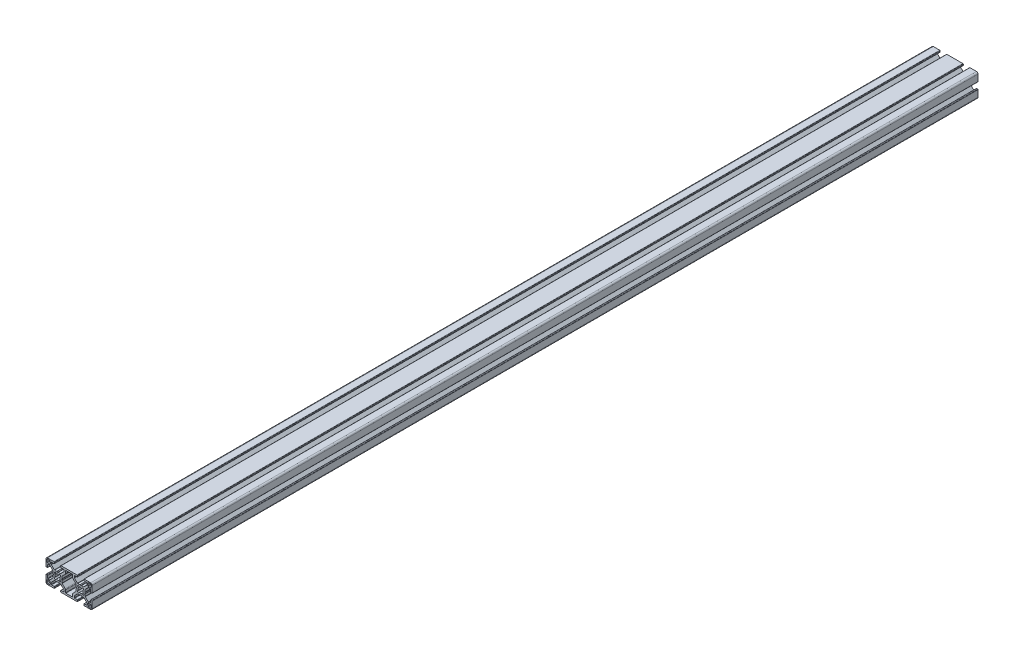
SolidWorks part; units mm, degrees
material "6105-T5 Aluminum"
ref_plane "Front Plane" through (0, 0, 0) normal (0, 0, 1) x (1, 0, 0)
ref_plane "Top Plane" through (0, 0, 0) normal (0, 1, 0) x (1, 0, 0)
ref_plane "Right Plane" through (0, 0, 0) normal (1, 0, 0) x (0, 0, -1)
sketch "Sketch1" plane through (0, 0, 0) normal (0, 0, 1) x (1, 0, 0)
  line L0 (12.7825, 3.7261) -> (13.5257, 2.983)
  line L1 (16.4743, 2.983) -> (17.2175, 3.7261)
  line L2 (18.7261, 2.2175) -> (17.983, 1.4743)
  line L3 (17.983, -1.4743) -> (18.7261, -2.2175)
  line L4 (17.2175, -3.7261) -> (16.4743, -2.983)
  line L5 (13.5257, -2.983) -> (12.7825, -3.7261)
  line L6 (11.2739, -2.2175) -> (12.017, -1.4743)
  line L7 (12.017, 1.4743) -> (11.2739, 2.2175)
  line L8 (-28.7046, 9.8946) -> (-28.7046, 12.6886)
  line L9 (-27.6886, 13.7046) -> (-24.8946, 13.7046)
  line L10 (-24.5136, 13.3236) -> (-24.5136, 9.8946)
  line L11 (-24.8946, 9.5136) -> (-28.3236, 9.5136)
  line L12 (-24.8946, -13.7046) -> (-27.6886, -13.7046)
  line L13 (-28.7046, -12.6886) -> (-28.7046, -9.8946)
  line L14 (-28.3236, -9.5136) -> (-24.8946, -9.5136)
  line L15 (-24.5136, -9.8946) -> (-24.5136, -13.3236)
  line L16 (4.9816, 8.2224) -> (9.0292, 4.1748)
  line L17 (9.178, 3.8155) -> (9.178, 0.9525)
  line L18 (9.178, 0.9525) -> (9.686, 0)
  line L19 (9.686, 0) -> (9.178, -0.9525)
  line L20 (9.178, -0.9525) -> (9.178, -3.8155)
  line L21 (9.0292, -4.1748) -> (4.9816, -8.2224)
  line L22 (4.5352, -9.3) -> (4.5352, -12.4092)
  line L23 (4.1542, -12.7902) -> (-4.1542, -12.7902)
  line L24 (-4.5352, -12.4092) -> (-4.5352, -9.3)
  line L25 (-4.9816, -8.2224) -> (-9.0292, -4.1748)
  line L26 (-9.178, -3.8155) -> (-9.178, -0.9525)
  line L27 (-9.178, -0.9525) -> (-9.686, 0)
  line L28 (-9.686, 0) -> (-9.178, 0.9525)
  line L29 (-9.178, 0.9525) -> (-9.178, 3.8155)
  line L30 (-9.0292, 4.1748) -> (-4.9816, 8.2224)
  line L31 (-4.5352, 9.3) -> (-4.5352, 12.4092)
  line L32 (-4.1542, 12.7902) -> (4.1542, 12.7902)
  line L33 (4.5352, 12.4092) -> (4.5352, 9.3)
  line L34 (-18.7261, -2.2175) -> (-17.983, -1.4743)
  line L35 (-17.983, 1.4743) -> (-18.7261, 2.2175)
  line L36 (-17.2175, 3.7261) -> (-16.4743, 2.983)
  line L37 (-13.5257, 2.983) -> (-12.7825, 3.7261)
  line L38 (-11.2739, 2.2175) -> (-12.017, 1.4743)
  line L39 (-12.017, -1.4743) -> (-11.2739, -2.2175)
  line L40 (-12.7825, -3.7261) -> (-13.5257, -2.983)
  line L41 (-16.4743, -2.983) -> (-17.2175, -3.7261)
  line L42 (24.8946, 13.7046) -> (27.6886, 13.7046)
  line L43 (28.7046, 12.6886) -> (28.7046, 9.8946)
  line L44 (28.3236, 9.5136) -> (24.8946, 9.5136)
  line L45 (24.5136, 9.8946) -> (24.5136, 13.3236)
  line L46 (24.5136, -13.3236) -> (24.5136, -9.8946)
  line L47 (24.8946, -9.5136) -> (28.3236, -9.5136)
  line L48 (28.7046, -9.8946) -> (28.7046, -12.6886)
  line L49 (27.6886, -13.7046) -> (24.8946, -13.7046)
  line L50 (-10.428, -15) -> (10.428, -15)
  line L51 (10.936, -14.492) -> (10.936, -13.2982)
  line L52 (10.428, -12.7902) -> (7.253, -12.7902)
  line L53 (6.745, -12.2822) -> (6.745, -10.2615)
  line L54 (6.8938, -9.9023) -> (10.8252, -5.9708)
  line L55 (11.1845, -5.822) -> (14.0475, -5.822)
  line L56 (14.0475, -5.822) -> (15, -5.314)
  line L57 (15, -5.314) -> (15.9525, -5.822)
  line L58 (15.9525, -5.822) -> (18.8155, -5.822)
  line L59 (19.1748, -5.9708) -> (23.1062, -9.9023)
  line L60 (23.255, -10.2615) -> (23.255, -12.2822)
  line L61 (22.747, -12.7902) -> (19.572, -12.7902)
  line L62 (19.064, -13.2982) -> (19.064, -14.492)
  line L63 (19.572, -15) -> (27.9934, -15)
  line L64 (30, -12.9934) -> (30, -4.572)
  line L65 (29.492, -4.064) -> (28.2982, -4.064)
  line L66 (27.7902, -4.572) -> (27.7902, -7.747)
  line L67 (27.2822, -8.255) -> (25.2615, -8.255)
  line L68 (24.9023, -8.1062) -> (20.9708, -4.1748)
  line L69 (20.822, -3.8155) -> (20.822, -0.9525)
  line L70 (20.822, -0.9525) -> (20.314, 0)
  line L71 (20.314, 0) -> (20.822, 0.9525)
  line L72 (20.822, 0.9525) -> (20.822, 3.8155)
  line L73 (20.9708, 4.1748) -> (24.9023, 8.1062)
  line L74 (25.2615, 8.255) -> (27.2822, 8.255)
  line L75 (27.7902, 7.747) -> (27.7902, 4.572)
  line L76 (28.2982, 4.064) -> (29.492, 4.064)
  line L77 (30, 4.572) -> (30, 12.9934)
  line L78 (27.9934, 15) -> (19.572, 15)
  line L79 (19.064, 14.492) -> (19.064, 13.2982)
  line L80 (19.572, 12.7902) -> (22.747, 12.7902)
  line L81 (23.255, 12.2822) -> (23.255, 10.2615)
  line L82 (23.1062, 9.9023) -> (19.1748, 5.9708)
  line L83 (18.8155, 5.822) -> (15.9525, 5.822)
  line L84 (15.9525, 5.822) -> (15, 5.314)
  line L85 (15, 5.314) -> (14.0475, 5.822)
  line L86 (14.0475, 5.822) -> (11.1845, 5.822)
  line L87 (10.8252, 5.9708) -> (6.8938, 9.9023)
  line L88 (6.745, 10.2615) -> (6.745, 12.2822)
  line L89 (7.253, 12.7902) -> (10.428, 12.7902)
  line L90 (10.936, 13.2982) -> (10.936, 14.492)
  line L91 (10.428, 15) -> (-10.428, 15)
  line L92 (-10.936, 14.492) -> (-10.936, 13.2982)
  line L93 (-10.428, 12.7902) -> (-7.253, 12.7902)
  line L94 (-6.745, 12.2822) -> (-6.745, 10.2615)
  line L95 (-6.8938, 9.9023) -> (-10.8252, 5.9708)
  line L96 (-11.1845, 5.822) -> (-14.0475, 5.822)
  line L97 (-14.0475, 5.822) -> (-15, 5.314)
  line L98 (-15, 5.314) -> (-15.9525, 5.822)
  line L99 (-15.9525, 5.822) -> (-18.8155, 5.822)
  line L100 (-19.1748, 5.9708) -> (-23.1062, 9.9023)
  line L101 (-23.255, 10.2615) -> (-23.255, 12.2822)
  line L102 (-22.747, 12.7902) -> (-19.572, 12.7902)
  line L103 (-19.064, 13.2982) -> (-19.064, 14.492)
  line L104 (-19.572, 15) -> (-27.9934, 15)
  line L105 (-30, 12.9934) -> (-30, 4.572)
  line L106 (-29.492, 4.064) -> (-28.2982, 4.064)
  line L107 (-27.7902, 4.572) -> (-27.7902, 7.747)
  line L108 (-27.2822, 8.255) -> (-25.2615, 8.255)
  line L109 (-24.9023, 8.1062) -> (-20.9708, 4.1748)
  line L110 (-20.822, 3.8155) -> (-20.822, 0.9525)
  line L111 (-20.822, 0.9525) -> (-20.314, 0)
  line L112 (-20.314, 0) -> (-20.822, -0.9525)
  line L113 (-20.822, -0.9525) -> (-20.822, -3.8155)
  line L114 (-20.9708, -4.1748) -> (-24.9023, -8.1062)
  line L115 (-25.2615, -8.255) -> (-27.2822, -8.255)
  line L116 (-27.7902, -7.747) -> (-27.7902, -4.572)
  line L117 (-28.2982, -4.064) -> (-29.492, -4.064)
  line L118 (-30, -4.572) -> (-30, -12.9934)
  line L119 (-27.9934, -15) -> (-19.572, -15)
  line L120 (-19.064, -14.492) -> (-19.064, -13.2982)
  line L121 (-19.572, -12.7902) -> (-22.747, -12.7902)
  line L122 (-23.255, -12.2822) -> (-23.255, -10.2615)
  line L123 (-23.1062, -9.9023) -> (-19.1748, -5.9708)
  line L124 (-18.8155, -5.822) -> (-15.9525, -5.822)
  line L125 (-15.9525, -5.822) -> (-15, -5.314)
  line L126 (-15, -5.314) -> (-14.0475, -5.822)
  line L127 (-14.0475, -5.822) -> (-11.1845, -5.822)
  line L128 (-10.8252, -5.9708) -> (-6.8938, -9.9023)
  line L129 (-6.745, -10.2615) -> (-6.745, -12.2822)
  line L130 (-7.253, -12.7902) -> (-10.428, -12.7902)
  line L131 (-10.936, -13.2982) -> (-10.936, -14.492)
  arc A0 (12.7825, 3.7261) -> (11.2739, 2.2175) centre (12.0282, 2.9718) ccw
  arc A1 (16.4743, 2.983) -> (13.5257, 2.983) centre (15, 0) ccw
  arc A2 (18.7261, 2.2175) -> (17.2175, 3.7261) centre (17.9718, 2.9718) ccw
  arc A3 (17.983, -1.4743) -> (17.983, 1.4743) centre (15, 0) ccw
  arc A4 (17.2175, -3.7261) -> (18.7261, -2.2175) centre (17.9718, -2.9718) ccw
  arc A5 (13.5257, -2.983) -> (16.4743, -2.983) centre (15, 0) ccw
  arc A6 (11.2739, -2.2175) -> (12.7825, -3.7261) centre (12.0282, -2.9718) ccw
  arc A7 (12.017, 1.4743) -> (12.017, -1.4743) centre (15, 0) ccw
  arc A8 (-28.7046, 9.8946) -> (-28.3236, 9.5136) centre (-28.3236, 9.8946) ccw
  arc A9 (-27.6886, 13.7046) -> (-28.7046, 12.6886) centre (-27.6886, 12.6886) ccw
  arc A10 (-24.5136, 13.3236) -> (-24.8946, 13.7046) centre (-24.8946, 13.3236) ccw
  arc A11 (-24.8946, 9.5136) -> (-24.5136, 9.8946) centre (-24.8946, 9.8946) ccw
  arc A12 (-24.8946, -13.7046) -> (-24.5136, -13.3236) centre (-24.8946, -13.3236) ccw
  arc A13 (-28.7046, -12.6886) -> (-27.6886, -13.7046) centre (-27.6886, -12.6886) ccw
  arc A14 (-28.3236, -9.5136) -> (-28.7046, -9.8946) centre (-28.3236, -9.8946) ccw
  arc A15 (-24.5136, -9.8946) -> (-24.8946, -9.5136) centre (-24.8946, -9.8946) ccw
  arc A16 (4.5352, 9.3) -> (4.9816, 8.2224) centre (6.0592, 9.3) ccw
  arc A17 (9.178, 3.8155) -> (9.0292, 4.1748) centre (8.67, 3.8155) ccw
  arc A18 (9.0292, -4.1748) -> (9.178, -3.8155) centre (8.67, -3.8155) ccw
  arc A19 (4.9816, -8.2224) -> (4.5352, -9.3) centre (6.0592, -9.3) ccw
  arc A20 (4.1542, -12.7902) -> (4.5352, -12.4092) centre (4.1542, -12.4092) ccw
  arc A21 (-4.5352, -12.4092) -> (-4.1542, -12.7902) centre (-4.1542, -12.4092) ccw
  arc A22 (-4.5352, -9.3) -> (-4.9816, -8.2224) centre (-6.0592, -9.3) ccw
  arc A23 (-9.178, -3.8155) -> (-9.0292, -4.1748) centre (-8.67, -3.8155) ccw
  arc A24 (-9.0292, 4.1748) -> (-9.178, 3.8155) centre (-8.67, 3.8155) ccw
  arc A25 (-4.9816, 8.2224) -> (-4.5352, 9.3) centre (-6.0592, 9.3) ccw
  arc A26 (-4.1542, 12.7902) -> (-4.5352, 12.4092) centre (-4.1542, 12.4092) ccw
  arc A27 (4.5352, 12.4092) -> (4.1542, 12.7902) centre (4.1542, 12.4092) ccw
  arc A28 (-18.7261, -2.2175) -> (-17.2175, -3.7261) centre (-17.9718, -2.9718) ccw
  arc A29 (-17.983, 1.4743) -> (-17.983, -1.4743) centre (-15, 0) ccw
  arc A30 (-17.2175, 3.7261) -> (-18.7261, 2.2175) centre (-17.9718, 2.9718) ccw
  arc A31 (-13.5257, 2.983) -> (-16.4743, 2.983) centre (-15, 0) ccw
  arc A32 (-11.2739, 2.2175) -> (-12.7825, 3.7261) centre (-12.0282, 2.9718) ccw
  arc A33 (-12.017, -1.4743) -> (-12.017, 1.4743) centre (-15, 0) ccw
  arc A34 (-12.7825, -3.7261) -> (-11.2739, -2.2175) centre (-12.0282, -2.9718) ccw
  arc A35 (-16.4743, -2.983) -> (-13.5257, -2.983) centre (-15, 0) ccw
  arc A36 (24.8946, 13.7046) -> (24.5136, 13.3236) centre (24.8946, 13.3236) ccw
  arc A37 (28.7046, 12.6886) -> (27.6886, 13.7046) centre (27.6886, 12.6886) ccw
  arc A38 (28.3236, 9.5136) -> (28.7046, 9.8946) centre (28.3236, 9.8946) ccw
  arc A39 (24.5136, 9.8946) -> (24.8946, 9.5136) centre (24.8946, 9.8946) ccw
  arc A40 (24.5136, -13.3236) -> (24.8946, -13.7046) centre (24.8946, -13.3236) ccw
  arc A41 (24.8946, -9.5136) -> (24.5136, -9.8946) centre (24.8946, -9.8946) ccw
  arc A42 (28.7046, -9.8946) -> (28.3236, -9.5136) centre (28.3236, -9.8946) ccw
  arc A43 (27.6886, -13.7046) -> (28.7046, -12.6886) centre (27.6886, -12.6886) ccw
  arc A44 (10.428, -15) -> (10.936, -14.492) centre (10.428, -14.492) ccw
  arc A45 (10.936, -13.2982) -> (10.428, -12.7902) centre (10.428, -13.2982) ccw
  arc A46 (6.745, -12.2822) -> (7.253, -12.7902) centre (7.253, -12.2822) ccw
  arc A47 (6.8938, -9.9023) -> (6.745, -10.2615) centre (7.253, -10.2615) ccw
  arc A48 (11.1845, -5.822) -> (10.8252, -5.9708) centre (11.1845, -6.33) ccw
  arc A49 (19.1748, -5.9708) -> (18.8155, -5.822) centre (18.8155, -6.33) ccw
  arc A50 (23.255, -10.2615) -> (23.1062, -9.9023) centre (22.747, -10.2615) ccw
  arc A51 (22.747, -12.7902) -> (23.255, -12.2822) centre (22.747, -12.2822) ccw
  arc A52 (19.572, -12.7902) -> (19.064, -13.2982) centre (19.572, -13.2982) ccw
  arc A53 (19.064, -14.492) -> (19.572, -15) centre (19.572, -14.492) ccw
  arc A54 (27.9934, -15) -> (30, -12.9934) centre (27.9934, -12.9934) ccw
  arc A55 (30, -4.572) -> (29.492, -4.064) centre (29.492, -4.572) ccw
  arc A56 (28.2982, -4.064) -> (27.7902, -4.572) centre (28.2982, -4.572) ccw
  arc A57 (27.2822, -8.255) -> (27.7902, -7.747) centre (27.2822, -7.747) ccw
  arc A58 (24.9023, -8.1062) -> (25.2615, -8.255) centre (25.2615, -7.747) ccw
  arc A59 (20.822, -3.8155) -> (20.9708, -4.1748) centre (21.33, -3.8155) ccw
  arc A60 (20.9708, 4.1748) -> (20.822, 3.8155) centre (21.33, 3.8155) ccw
  arc A61 (25.2615, 8.255) -> (24.9023, 8.1062) centre (25.2615, 7.747) ccw
  arc A62 (27.7902, 7.747) -> (27.2822, 8.255) centre (27.2822, 7.747) ccw
  arc A63 (27.7902, 4.572) -> (28.2982, 4.064) centre (28.2982, 4.572) ccw
  arc A64 (29.492, 4.064) -> (30, 4.572) centre (29.492, 4.572) ccw
  arc A65 (30, 12.9934) -> (27.9934, 15) centre (27.9934, 12.9934) ccw
  arc A66 (19.572, 15) -> (19.064, 14.492) centre (19.572, 14.492) ccw
  arc A67 (19.064, 13.2982) -> (19.572, 12.7902) centre (19.572, 13.2982) ccw
  arc A68 (23.255, 12.2822) -> (22.747, 12.7902) centre (22.747, 12.2822) ccw
  arc A69 (23.1062, 9.9023) -> (23.255, 10.2615) centre (22.747, 10.2615) ccw
  arc A70 (18.8155, 5.822) -> (19.1748, 5.9708) centre (18.8155, 6.33) ccw
  arc A71 (10.8252, 5.9708) -> (11.1845, 5.822) centre (11.1845, 6.33) ccw
  arc A72 (6.745, 10.2615) -> (6.8938, 9.9023) centre (7.253, 10.2615) ccw
  arc A73 (7.253, 12.7902) -> (6.745, 12.2822) centre (7.253, 12.2822) ccw
  arc A74 (10.428, 12.7902) -> (10.936, 13.2982) centre (10.428, 13.2982) ccw
  arc A75 (10.936, 14.492) -> (10.428, 15) centre (10.428, 14.492) ccw
  arc A76 (-10.428, 15) -> (-10.936, 14.492) centre (-10.428, 14.492) ccw
  arc A77 (-10.936, 13.2982) -> (-10.428, 12.7902) centre (-10.428, 13.2982) ccw
  arc A78 (-6.745, 12.2822) -> (-7.253, 12.7902) centre (-7.253, 12.2822) ccw
  arc A79 (-6.8938, 9.9023) -> (-6.745, 10.2615) centre (-7.253, 10.2615) ccw
  arc A80 (-11.1845, 5.822) -> (-10.8252, 5.9708) centre (-11.1845, 6.33) ccw
  arc A81 (-19.1748, 5.9708) -> (-18.8155, 5.822) centre (-18.8155, 6.33) ccw
  arc A82 (-23.255, 10.2615) -> (-23.1062, 9.9023) centre (-22.747, 10.2615) ccw
  arc A83 (-22.747, 12.7902) -> (-23.255, 12.2822) centre (-22.747, 12.2822) ccw
  arc A84 (-19.572, 12.7902) -> (-19.064, 13.2982) centre (-19.572, 13.2982) ccw
  arc A85 (-19.064, 14.492) -> (-19.572, 15) centre (-19.572, 14.492) ccw
  arc A86 (-27.9934, 15) -> (-30, 12.9934) centre (-27.9934, 12.9934) ccw
  arc A87 (-30, 4.572) -> (-29.492, 4.064) centre (-29.492, 4.572) ccw
  arc A88 (-28.2982, 4.064) -> (-27.7902, 4.572) centre (-28.2982, 4.572) ccw
  arc A89 (-27.2822, 8.255) -> (-27.7902, 7.747) centre (-27.2822, 7.747) ccw
  arc A90 (-24.9023, 8.1062) -> (-25.2615, 8.255) centre (-25.2615, 7.747) ccw
  arc A91 (-20.822, 3.8155) -> (-20.9708, 4.1748) centre (-21.33, 3.8155) ccw
  arc A92 (-20.9708, -4.1748) -> (-20.822, -3.8155) centre (-21.33, -3.8155) ccw
  arc A93 (-25.2615, -8.255) -> (-24.9023, -8.1062) centre (-25.2615, -7.747) ccw
  arc A94 (-27.7902, -7.747) -> (-27.2822, -8.255) centre (-27.2822, -7.747) ccw
  arc A95 (-27.7902, -4.572) -> (-28.2982, -4.064) centre (-28.2982, -4.572) ccw
  arc A96 (-29.492, -4.064) -> (-30, -4.572) centre (-29.492, -4.572) ccw
  arc A97 (-30, -12.9934) -> (-27.9934, -15) centre (-27.9934, -12.9934) ccw
  arc A98 (-19.572, -15) -> (-19.064, -14.492) centre (-19.572, -14.492) ccw
  arc A99 (-19.064, -13.2982) -> (-19.572, -12.7902) centre (-19.572, -13.2982) ccw
  arc A100 (-23.255, -12.2822) -> (-22.747, -12.7902) centre (-22.747, -12.2822) ccw
  arc A101 (-23.1062, -9.9023) -> (-23.255, -10.2615) centre (-22.747, -10.2615) ccw
  arc A102 (-18.8155, -5.822) -> (-19.1748, -5.9708) centre (-18.8155, -6.33) ccw
  arc A103 (-10.8252, -5.9708) -> (-11.1845, -5.822) centre (-11.1845, -6.33) ccw
  arc A104 (-6.745, -10.2615) -> (-6.8938, -9.9023) centre (-7.253, -10.2615) ccw
  arc A105 (-7.253, -12.7902) -> (-6.745, -12.2822) centre (-7.253, -12.2822) ccw
  arc A106 (-10.428, -12.7902) -> (-10.936, -13.2982) centre (-10.428, -13.2982) ccw
  arc A107 (-10.936, -14.492) -> (-10.428, -15) centre (-10.428, -14.492) ccw
extrude "Extrude1" add sketch "Sketch1" against normal blind 1150
sketch "Sketch2" plane through (0, 15, 0) normal (0, 1, 0) x (1, 0, 0)
  line L1 (-19.572, 1150) -> (-27.9934, 1150) construction
  line L2 (15, 1150) -> (15, 0) construction
  line L3 (15, 1150) -> (15, 0) construction
  circle A0 centre (15, 781) radius 3.175
  circle A1 centre (15, 369) radius 3.175
  dimension "D1" = 6.35
  dimension "D2" = 369
  dimension "D3" = 369
extrude "Cut-Extrude1" cut sketch "Sketch2" against normal through all
